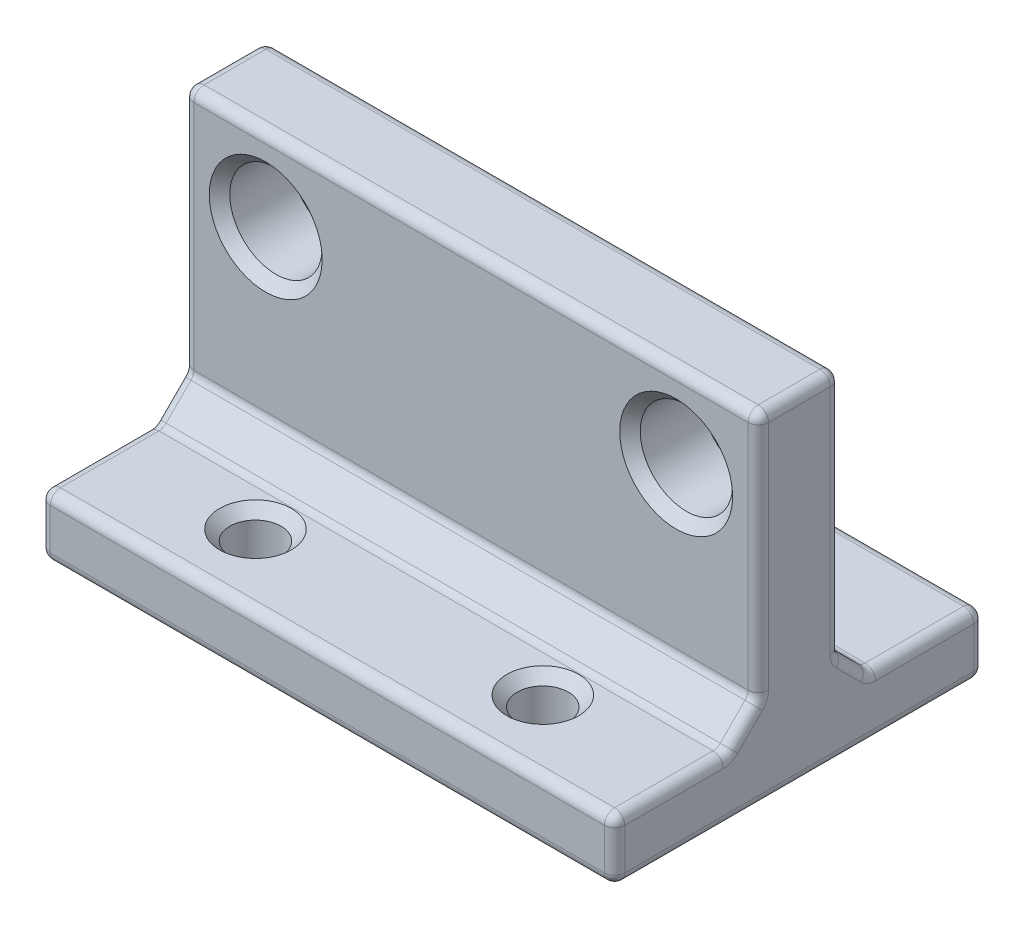
SolidWorks part; units mm, degrees
ref_plane "前视基准面" through (0, 0, 0) normal (0, 0, 1) x (1, 0, 0)
ref_plane "上视基准面" through (0, 0, 0) normal (0, 1, 0) x (1, 0, 0)
ref_plane "右视基准面" through (0, 0, 0) normal (1, 0, 0) x (0, 0, -1)
other "Configuration Table"
sketch "草图1" plane through (0, 0, 0) normal (0, 1, 0) x (1, 0, 0)
  line L1 (-7, -5.5) -> (7, -5.5) construction
  line L2 (-7, -5.5) -> (-7, 5.5) construction
  line L3 (-7, 5.5) -> (7, 5.5) construction
  line L4 (7, -5.5) -> (7, 5.5) construction
  line L5 (-7, -5.5) -> (7, 5.5) construction
  line L6 (-7, 5.5) -> (7, -5.5) construction
  circle A0 centre (-7, 5.5) radius 1.25
  circle A1 centre (-7, -5.5) radius 1.25
  circle A2 centre (7, -5.5) radius 1.25
  circle A3 centre (7, 5.5) radius 1.25
  point P0 (0, 0)
  dimension "D3" = 2.5
  dimension "D1" = 14
  dimension "D2" = 11
sketch "草图2" plane through (0, 0, 0) normal (0, 0, 1) x (1, 0, 0)
  line L0 (0, 0) -> (0, 50000) construction
  line L1 (-14, -7.5) -> (14, -7.5)
  line L2 (-14, -7.5) -> (-14, 7.5)
  line L3 (-14, 7.5) -> (14, 7.5)
  line L4 (14, -7.5) -> (14, 7.5)
  line L5 (-14, -7.5) -> (14, 7.5) construction
  line L6 (-14, 7.5) -> (14, -7.5) construction
  circle A0 centre (-10, 3.5) radius 2.25
  circle A1 centre (10, 3.5) radius 2.25
  point P0 (0, 0)
  point P12 (0, 0)
  point P13 (9.383, 0)
  point P14 (10, 2.8084)
  dimension "D4" = 4.5
  dimension "D1" = 28
  dimension "D2" = 15
  dimension "D3" = 10
  dimension "D5" = 20
  dimension "D6" = 4
extrude "凸台-拉伸1" add sketch "草图2" along normal mid plane 4
sketch "草图3" plane through (0, -7.5, 0) normal (0, -1, 0) x (1, 0, 0)
  line L0 (-7, 5.5) -> (7, -5.5) construction
  line L1 (-14, -9) -> (14, -9)
  line L2 (-14, -9) -> (-14, 9)
  line L3 (-14, 9) -> (14, 9)
  line L4 (14, -9) -> (14, 9)
  line L5 (-14, -9) -> (14, 9) construction
  line L6 (-14, 9) -> (14, -9) construction
  line L7 (-14, 2) -> (-14, -2) construction
  point P0 (0, 0)
  dimension "D1" = 18
extrude "凸台-拉伸2" add sketch "草图3" along normal mid plane 3
chamfer "倒角1" distance 1.5 angle 45 2 edges at (0, -6, -2) (0, -6, 2)
extrude "切除-拉伸1" cut sketch "草图1" against normal blind 109
fillet "圆角1" radius 0.5 30 edges at (0, -9, 9) (0, -6, 9) (0, -9, -9) (0, -6, -9) (0, -6, -3.5) (0, -4.5, -2) (0, -4.5, 2) (0, -6, 3.5) (14, 1.5, -2) (14, -5.25, -2.75) (14, -6, -6.25) (14, -7.5, -9) (14, -9, 0) (14, -7.5, 9) (14, -6, 6.25) (14, -5.25, 2.75) (14, 1.5, 2) (14, 7.5, 0) (0, 7.5, 2) (0, 7.5, -2) (-14, 7.5, 0) (-14, 1.5, 2) (-14, -5.25, 2.75) (-14, -6, 6.25) (-14, -7.5, 9) (-14, -9, 0) (-14, -7.5, -9) (-14, -6, -6.25) (-14, -5.25, -2.75) (-14, 1.5, -2)
chamfer "倒角2" distance 0.5 angle 45 12 edges at (7, -9, -4.25) (7, -6, -4.25) (-7, -9, -4.25) (-7, -6, -4.25) (7, -9, 6.75) (7, -6, 6.75) (-7, -9, 6.75) (-7, -6, 6.75) (12.25, 3.5, -2) (12.25, 3.5, 2) (-7.75, 3.5, -2) (-7.75, 3.5, 2)
